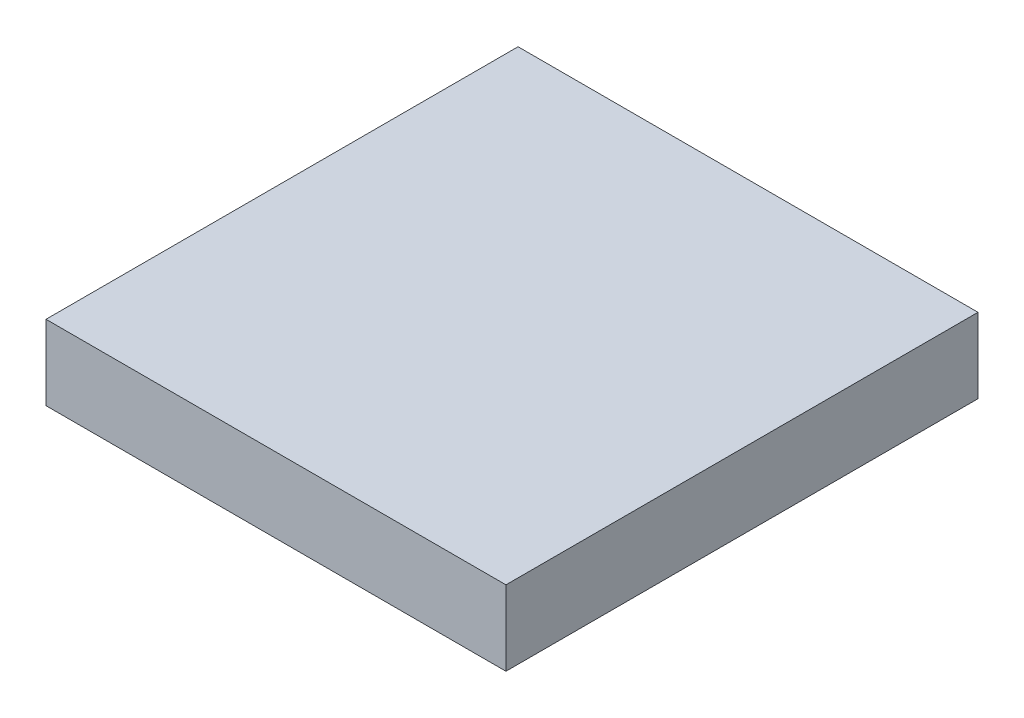
SolidWorks part; units mm, degrees
ref_plane "Front Plane" through (0, 0, 0) normal (0, 0, 1) x (1, 0, 0)
ref_plane "Top Plane" through (0, 0, 0) normal (0, 1, 0) x (1, 0, 0)
ref_plane "Right Plane" through (0, 0, 0) normal (1, 0, 0) x (0, 0, -1)
sketch "Sketch1" plane through (0, 0, 0) normal (0, 1, 0) x (1, 0, 0)
  line L1 (-15.3609, -15.7651) -> (15.3609, -15.7651)
  line L2 (-15.3609, -15.7651) -> (-15.3609, 15.7651)
  line L3 (-15.3609, 15.7651) -> (15.3609, 15.7651)
  line L4 (15.3609, -15.7651) -> (15.3609, 15.7651)
  line L5 (-15.3609, -15.7651) -> (15.3609, 15.7651) construction
  line L6 (-15.3609, 15.7651) -> (15.3609, -15.7651) construction
  point P0 (0, 0)
extrude "Boss-Extrude1" add sketch "Sketch1" along normal blind 5
